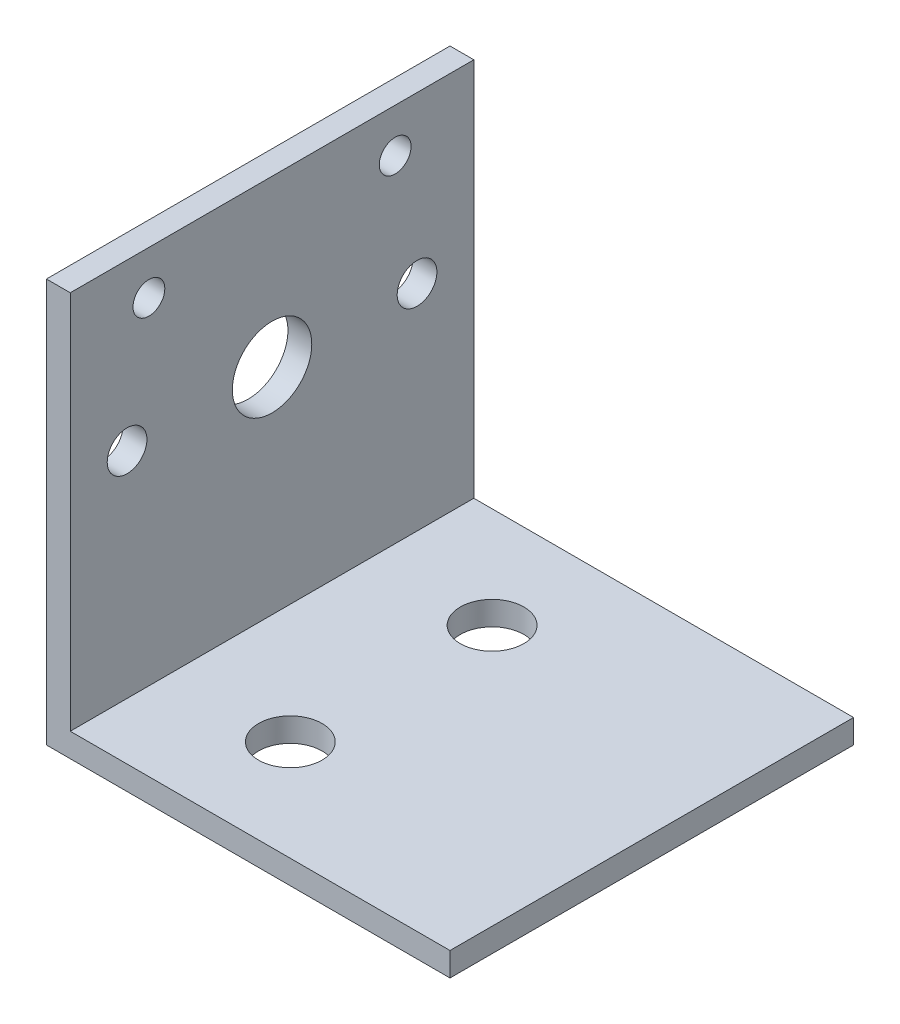
SolidWorks part; units mm, degrees
material "6061-T4 (SS)"
ref_plane "Front Plane" through (0, 0, 0) normal (0, 0, 1) x (1, 0, 0)
ref_plane "Top Plane" through (0, 0, 0) normal (0, 1, 0) x (1, 0, 0)
ref_plane "Right Plane" through (0, 0, 0) normal (1, 0, 0) x (0, 0, -1)
sketch "Sketch1" plane through (0, 0, 0) normal (0, 0, 1) x (1, 0, 0)
  line L0 (0, 0) -> (0, 50.8)
  line L1 (0, 0) -> (50.8, 0)
  dimension "D1" = 50.8
  dimension "D2" = 50.8
extrude "Extrude-Thin1" add sketch "Sketch1" along normal mid plane 50.8 thin
sketch "Sketch2" plane through (0, 0, 0) normal (-1, 0, 0) x (0, 0, 1)
  line L0 (-25.4, 30) -> (25.4, 30) construction
  line L3 (0, 50.8) -> (0, 0) construction
  line L4 (25.4, 50.8) -> (-25.4, 50.8) construction
  line L5 (25.4, 0) -> (-25.4, 0) construction
  line L6 (-25.4, 50.8) -> (-25.4, 0) construction
  circle A0 centre (-18.25, 30) radius 2.5
  circle A1 centre (18.25, 30) radius 2.5
  circle A2 centre (0, 30) radius 5
  dimension "D2" = 5
  dimension "D3" = 10
  dimension "D1" = 36.5
  dimension "D4" = 30
extrude "Cut-Extrude1" cut sketch "Sketch2" against normal up to next
sketch "Sketch3" plane through (0, 0, 0) normal (0, -1, 0) x (1, 0, 0)
  line L0 (18, 25.4) -> (18, -25.4) construction
  line L1 (0, 0) -> (50.8, 0) construction
  line L2 (50.8, 25.4) -> (50.8, -25.4) construction
  line L8 (0, 25.4) -> (50.8, 25.4) construction
  line L9 (0, 25.4) -> (0, -25.4) construction
  circle A0 centre (18, 12.7) radius 4
  circle A1 centre (18, -12.7) radius 4
  dimension "D2" = 8
  dimension "D1" = 25.4
  dimension "D3" = 18
extrude "Cut-Extrude2" cut sketch "Sketch3" against normal up to next
sketch "Sketch4" plane through (0, 0, 0) normal (-1, 0, 0) x (0, 0, 1)
  line L0 (0, 0) -> (0, 50.8) construction
  line L1 (25.4, 50.8) -> (-25.4, 50.8) construction
  line L2 (-15.5, 45.3) -> (15.5, 45.3) construction
  circle A0 centre (-15.5, 45.3) radius 2
  circle A1 centre (15.5, 45.3) radius 2
  dimension "D1" = 4
  dimension "D2" = 31
  dimension "D3" = 5.5
extrude "Cut-Extrude3" cut sketch "Sketch4" against normal up to next
